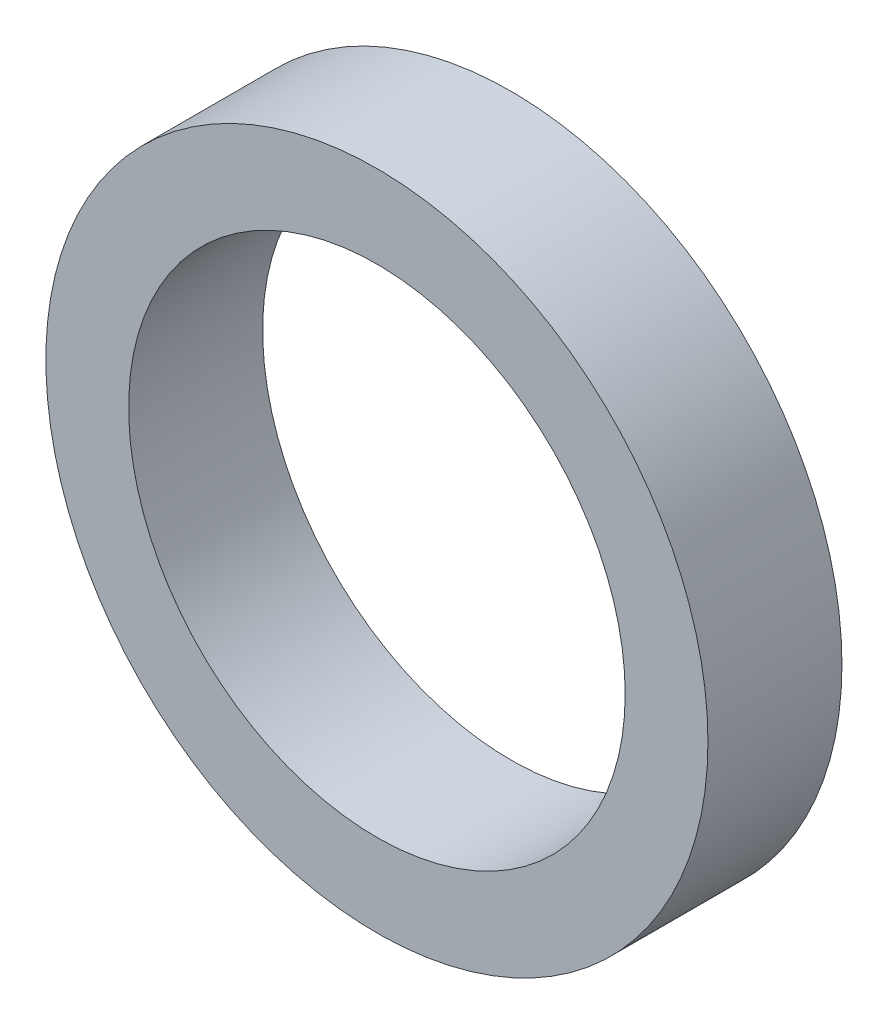
SolidWorks part; units mm, degrees
ref_plane "Front Plane" through (0, 0, 0) normal (0, 0, 1) x (1, 0, 0)
ref_plane "Top Plane" through (0, 0, 0) normal (0, 1, 0) x (1, 0, 0)
ref_plane "Right Plane" through (0, 0, 0) normal (1, 0, 0) x (0, 0, -1)
sketch "Sketch1" plane through (0, 0, 0) normal (0, 0, 1) x (1, 0, 0)
  circle A0 centre (0, 0) radius 3.15
  circle A1 centre (0, 0) radius 4.2
  dimension "D1" = 6.3
  dimension "D2" = 8.4
extrude "Boss-Extrude1" add sketch "Sketch1" along normal blind 1.7
